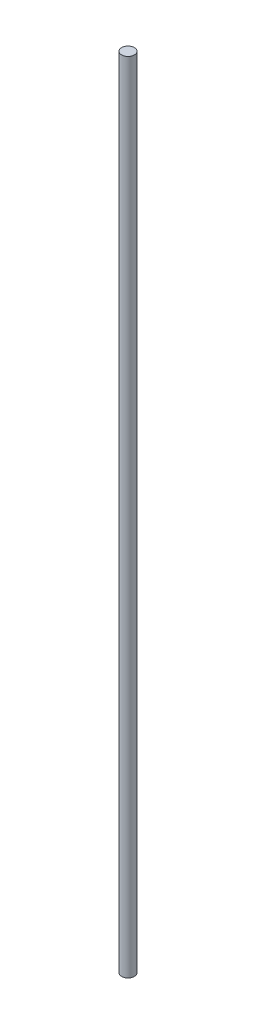
SolidWorks part; units mm, degrees
ref_plane "前视基准面" through (0, 0, 0) normal (0, 0, 1) x (1, 0, 0)
ref_plane "上视基准面" through (0, 0, 0) normal (0, 1, 0) x (1, 0, 0)
ref_plane "右视基准面" through (0, 0, 0) normal (1, 0, 0) x (0, 0, -1)
other "Configuration Table"
sketch "草图1" plane through (0, 0, 0) normal (0, 1, 0) x (1, 0, 0)
  circle A0 centre (0, 0) radius 2
extrude "凸台-拉伸1" add sketch "草图1" along normal blind 250
